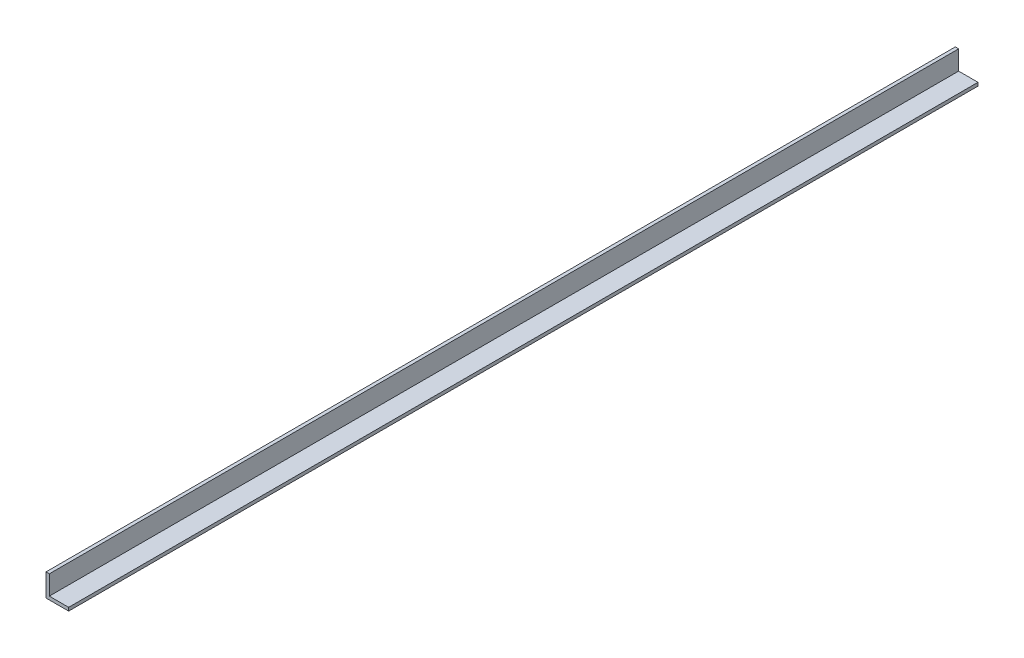
SolidWorks part; units mm, degrees
material "ASTM A36 Acero"
ref_plane "Alzado" through (0, 0, 0) normal (0, 0, 1) x (1, 0, 0)
ref_plane "Planta" through (0, 0, 0) normal (0, 1, 0) x (1, 0, 0)
ref_plane "Vista lateral" through (0, 0, 0) normal (1, 0, 0) x (0, 0, -1)
sketch "Croquis1" plane through (0, 0, 0) normal (0, 0, 1) x (1, 0, 0)
  line L0 (0, 152) -> (0, 0)
  line L1 (0, 0) -> (152, 0)
  line L2 (152, 0) -> (152, 22.23)
  line L3 (152, 22.23) -> (22.23, 22.23)
  line L4 (22.23, 22.23) -> (22.23, 152)
  line L5 (22.23, 152) -> (0, 152)
  dimension "D1" = 22.23
  dimension "D2" = 152
extrude "Saliente-Extruir1" add sketch "Croquis1" against normal blind 6100
